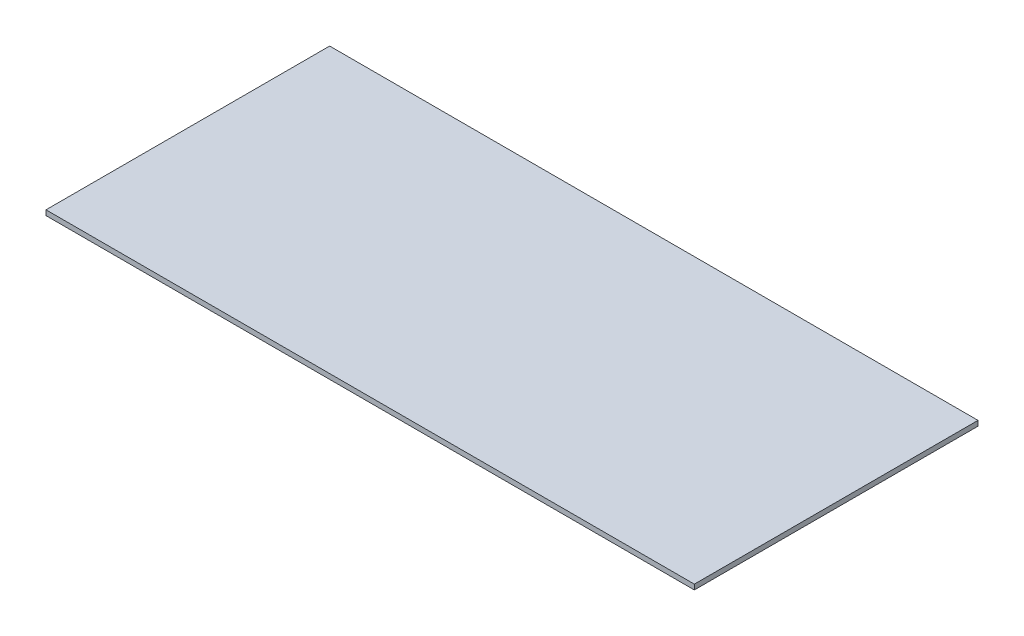
SolidWorks part; units mm, degrees
other "Markup1"
sketch "Sketch3" plane through (101.6, 1.5875, 19.05) normal (0.2772, 0.7582, 0.5902) x (0.9082, -0.0061, -0.4186)
ref_plane "Front Plane" through (0, 0, 0) normal (0, 0, 1) x (1, 0, 0)
ref_plane "Top Plane" through (0, 0, 0) normal (0, 1, 0) x (1, 0, 0)
ref_plane "Right Plane" through (0, 0, 0) normal (1, 0, 0) x (0, 0, -1)
sketch "Sketch2" plane through (0, 0, 0) normal (0, 1, 0) x (1, 0, 0)
  line L1 (-101.6, -44.45) -> (101.6, -44.45)
  line L2 (-101.6, -44.45) -> (-101.6, 44.45)
  line L3 (-101.6, 44.45) -> (101.6, 44.45)
  line L4 (101.6, -44.45) -> (101.6, 44.45)
  line L5 (-101.6, -44.45) -> (101.6, 44.45) construction
  line L6 (-101.6, 44.45) -> (101.6, -44.45) construction
  point P0 (0, 0)
  dimension "D1" = 88.9
  dimension "D2" = 203.2
extrude "Boss-Extrude1" add sketch "Sketch2" along normal blind 1.5875
sketch "Sketch4" plane through (0, 1.5875, 0) normal (0, 1, 0) x (1, 0, 0)
  line L0 (25.4, 44.45) -> (25.4, -44.45)
  line L1 (101.6, 44.45) -> (-101.6, 44.45) construction
  line L2 (-101.6, -44.45) -> (101.6, -44.45) construction
  line L3 (101.6, -44.45) -> (101.6, 44.45) construction
  dimension "D1" = 76.2
